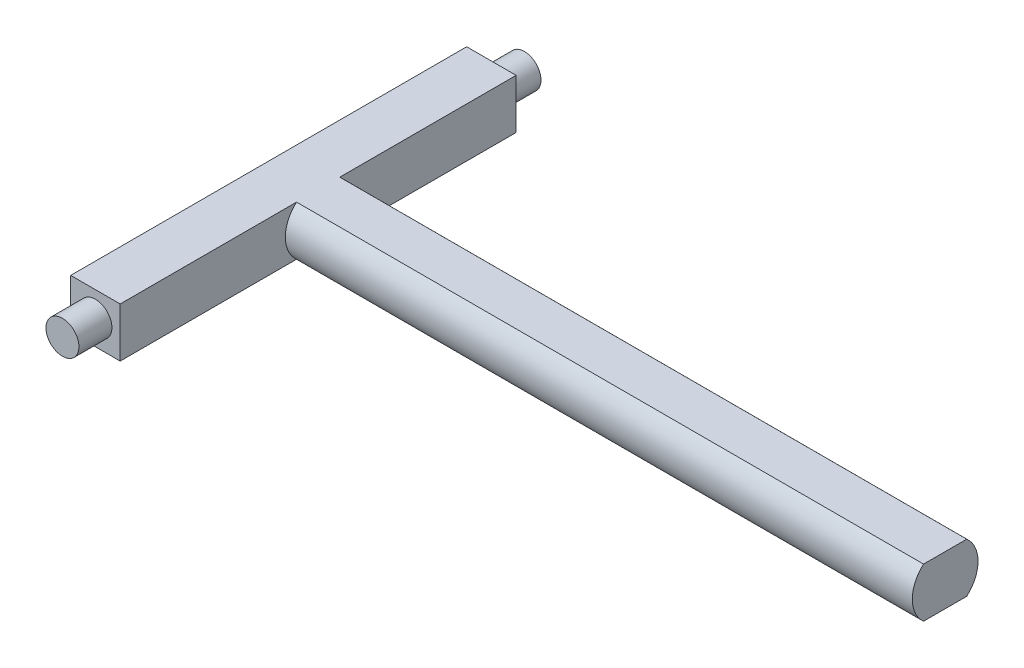
SolidWorks part; units mm, degrees
ref_plane "Front Plane" through (0, 0, 0) normal (0, 0, 1) x (1, 0, 0)
ref_plane "Top Plane" through (0, 0, 0) normal (0, 1, 0) x (1, 0, 0)
ref_plane "Right Plane" through (0, 0, 0) normal (1, 0, 0) x (0, 0, -1)
sketch "Sketch1" plane through (0, 0, 0) normal (1, 0, 0) x (0, 0, -1)
  line L0 (152.4, 0) -> (-152.4, 0)
  line L1 (-152.4, 0) -> (-152.4, 38.1)
  line L2 (-152.4, 38.1) -> (152.4, 38.1)
  line L3 (152.4, 38.1) -> (152.4, 0)
  point P4 (0, 0)
  dimension "D1" = 38.1
  dimension "D2" = 304.8
extrude "Boss-Extrude5" add sketch "Sketch1" along normal blind 38.1
sketch "Sketch7" plane through (0, 0, 152.4) normal (0, 0, 1) x (1, 0, 0)
  line L0 (0, 38.1) -> (38.1, 0)
  line L1 (38.1, 38.1) -> (0, 0)
  circle A0 centre (19.05, 19.05) radius 12.6739
extrude "Boss-Extrude6" add sketch "Sketch7" along normal blind 25.4 contours L1 A0 L0 | L0 A0 L1 | L1 A0 L0 | L0 A0 L1
sketch "Sketch8" plane through (0, 0, -152.4) normal (0, 0, -1) x (-1, 0, 0)
  line L0 (-38.1, 38.1) -> (0, 0)
  line L1 (0, 38.1) -> (-38.1, 0)
  circle A0 centre (-19.05, 19.05) radius 12.7359
extrude "Boss-Extrude7" add sketch "Sketch8" along normal blind 25.4 contours L1 A0 L0 | L0 A0 L1 | L1 A0 L0 | L0 A0 L1
sketch "Sketch9" plane through (38.1, 0, 0) normal (1, 0, 0) x (0, 0, -1)
  line L0 (0, 0) -> (0, 38.1)
  line L1 (152.4, 38.1) -> (-152.4, 38.1) construction
  circle A0 centre (0, 19.05) radius 25.2842
  line M2 (-152.4, 0) -> (152.4, 0)
  line M4 (152.4, 38.1) -> (-152.4, 38.1)
extrude "Boss-Extrude8" add sketch "Sketch9" along normal blind 482.6 contours A0 L0 M2 M4 | A0 L0 M4 M2
